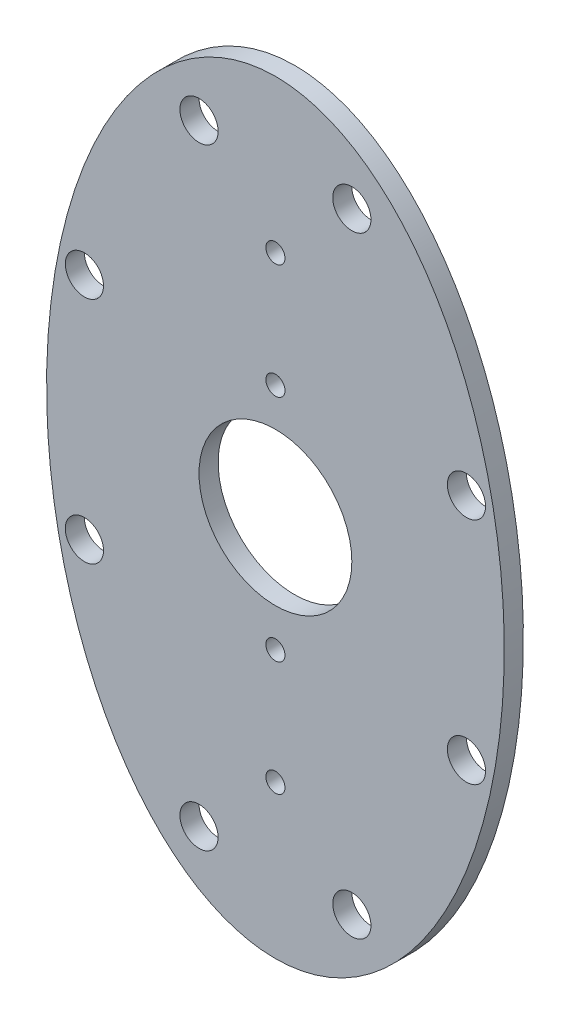
SolidWorks part; units mm, degrees
ref_plane "Front Plane" through (0, 0, 0) normal (1, 0, 0) x (0, 1, 0)
ref_plane "Top Plane" through (0, 0, 0) normal (0, 0, 1) x (0, 1, 0)
ref_plane "Right Plane" through (0, 0, 0) normal (0, 1, 0) x (-1, 0, 0)
sketch "Sketch2" plane through (0, 0, 0) normal (0, 0, 1) x (0, 1, 0)
  ellipse E0 centre (0, 0) end of major axis (254, 0) minor radius 152.1434
  dimension "D1" = 254
extrude "Boss-Extrude2" add sketch "Sketch2" along normal blind 12.7
sketch "Sketch3" plane through (0, 0, 12.7) normal (0, 0, 1) x (1, 0, 0)
  line L0 (0, 328.8829) -> (0, -410.4897) construction
  circle A0 centre (0, 0) radius 50.8
  circle A1 centre (-50.8, 203.2) radius 12.7
  circle A2 centre (50.8, 203.2) radius 12.7
  circle A3 centre (127, 76.2) radius 12.7
  circle A4 centre (127, -76.2) radius 12.7
  circle A5 centre (-50.8, -203.2) radius 12.7
  circle A6 centre (50.8, -203.2) radius 12.7
  circle A7 centre (-127, 76.2) radius 12.7
  circle A8 centre (-127, -76.2) radius 12.7
  circle A9 centre (0, 76.2) radius 6.35
  circle A11 centre (0, -76.2) radius 6.35
  circle A12 centre (0, 152.4) radius 6.35
  circle A13 centre (0, -152.4) radius 6.35
  point P22 (25.4, -103.9233)
  point P23 (25.0215, 84.3559)
  dimension "D1" = 25.4
  dimension "D2" = 25.4
  dimension "D3" = 25.4
  dimension "D4" = 25.4
  dimension "D5" = 25.4
  dimension "D6" = 25.4
  dimension "D7" = 25.4
  dimension "D8" = 25.4
  dimension "D17" = 101.6
  dimension "D18" = 12.7
  dimension "D19" = 12.7
  dimension "D22" = 12.7
  dimension "D23" = 12.7
  dimension "D9" = 76.2
  dimension "D10" = 76.2
  dimension "D11" = 50.8
  dimension "D12" = 50.8
  dimension "D13" = 203.2
  dimension "D14" = 203.2
  dimension "D15" = 127
  dimension "D16" = 127
  dimension "D20" = 76.2
  dimension "D21" = 76.2
  dimension "D24" = 152.4
  dimension "D25" = 152.4
extrude "Cut-Extrude1" cut sketch "Sketch3" against normal blind 12.7
